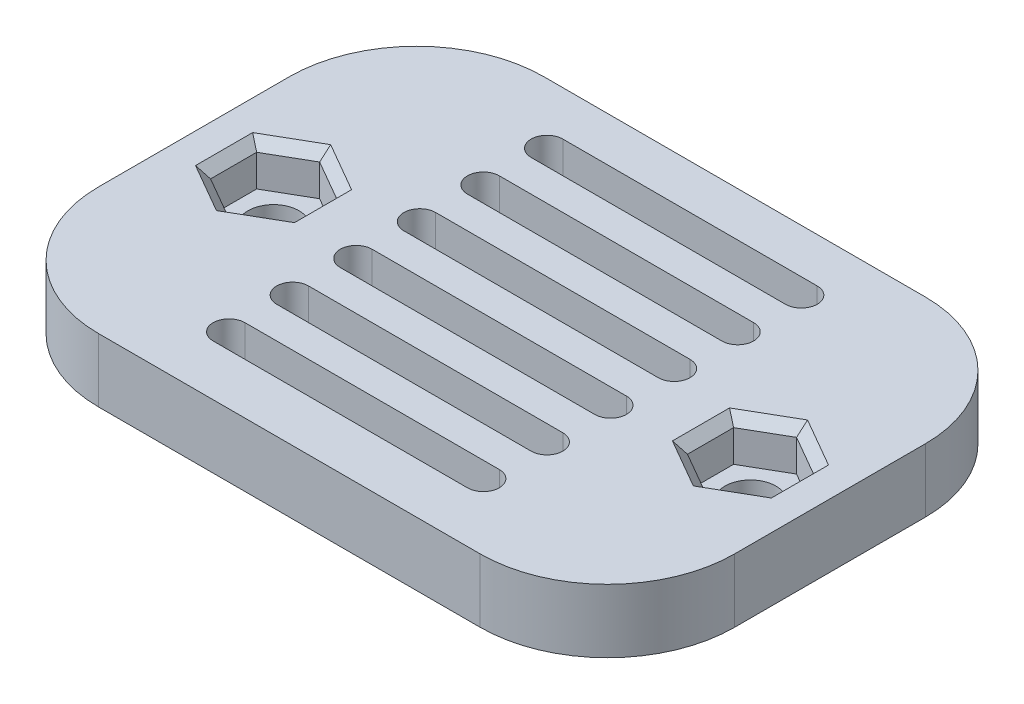
SolidWorks part; units mm, degrees
ref_plane "Alzado" through (0, 0, 0) normal (0, 0, 1) x (1, 0, 0)
ref_plane "Planta" through (0, 0, 0) normal (0, 1, 0) x (1, 0, 0)
ref_plane "Vista lateral" through (0, 0, 0) normal (1, 0, 0) x (0, 0, -1)
sketch "Croquis1" plane through (0, 0, 0) normal (0, 1, 0) x (1, 0, 0)
  line L1 (0, 0) -> (100, 0)
  line L2 (0, 0) -> (0, 70)
  line L3 (0, 70) -> (100, 70)
  line L4 (100, 0) -> (100, 70)
  dimension "D1" = 70
  dimension "D2" = 100
extrude "Saliente-Extruir1" add sketch "Croquis1" along normal blind 10
sketch "Croquis2" plane through (0, 10, 0) normal (0, 1, 0) x (1, 0, 0)
  line L0 (25, 70) -> (25, 0) construction
  line L1 (100, 70) -> (0, 70) construction
  line L2 (0, 0) -> (100, 0) construction
  line L3 (0, 70) -> (0, 0) construction
  line L4 (50, 70) -> (50, 0) construction
  line L5 (25, 70) -> (0, 70) construction
  line L6 (12.5, 70) -> (12.5, 0) construction
  line L7 (12.5, 35) -> (25, 35) construction
  line L9 (12.5, 42.25) -> (6.2213, 38.625)
  line L10 (6.2213, 38.625) -> (6.2213, 31.375)
  line L11 (6.2213, 31.375) -> (12.5, 27.75)
  line L12 (12.5, 27.75) -> (18.7787, 31.375)
  line L13 (18.7787, 31.375) -> (18.7787, 38.625)
  line L14 (18.7787, 38.625) -> (12.5, 42.25)
  circle A0 centre (12.5, 35) radius 6.2787 construction
  dimension "D1" = 25
  dimension "D2" = 14.5
extrude "Cortar-Extruir1" cut sketch "Croquis2" against normal blind 6.5
sketch "Croquis5" plane through (0, 10, 0) normal (0, 1, 0) x (1, 0, 0)
  circle A0 centre (12.5, 35) radius 4
extrude "Cortar-Extruir2" cut sketch "Croquis5" against normal up to surface (10 mm away) up to face at (50, 0, -35)
chamfer "Chaflán1" distance 1.5 angle 45 6 edges at (18.7787, 10, -35) (15.6393, 10, -29.5625) (9.3607, 10, -29.5625) (6.2213, 10, -35) (9.3607, 10, -40.4375) (15.6393, 10, -40.4375)
sketch "Croquis6" plane through (0, 10, 0) normal (0, 1, 0) x (1, 0, 0)
  line L0 (50, 70) -> (50, 0) construction
  line L1 (100, 70) -> (0, 70) construction
  line L2 (0, 0) -> (100, 0) construction
ref_plane "Plano1" through (50, 0, 0) normal (-1, 0, 0) x (0, 0, 1)
mirror "Simetría1" about plane through (50, 0, 0) normal (-1, 0, 0) of "Chaflán1", "Cortar-Extruir1", "Cortar-Extruir2"
fillet "Redondeo4" radius 20 1 edges at (100, 5, -70)
fillet "Redondeo5" radius 20 1 edges at (100, 5, 0)
fillet "Redondeo6" radius 20 1 edges at (0, 5, 0)
fillet "Redondeo7" radius 20 1 edges at (0, 5, -70)
sketch "Croquis7" plane through (0, 10, 0) normal (0, 1, 0) x (1, 0, 0)
  line L0 (50, 70) -> (50, 0) construction
  line L1 (80, 70) -> (20, 70) construction
  line L2 (20, 0) -> (80, 0) construction
  line L3 (25, 70) -> (25, 0) construction
  line L4 (75, 70) -> (75, 0) construction
  line L5 (30, 10.5) -> (70, 10.5) construction
  line L6 (30, 13) -> (70, 13)
  line L7 (30, 8) -> (70, 8)
  line L8 (30, 18) -> (70, 18)
  line L9 (30, 23) -> (70, 23)
  line L10 (30, 20.5) -> (70, 20.5) construction
  line L11 (30, 28) -> (70, 28)
  line L12 (30, 33) -> (70, 33)
  line L13 (30, 30.5) -> (70, 30.5) construction
  line L14 (30, 38) -> (70, 38)
  line L15 (30, 43) -> (70, 43)
  line L16 (30, 40.5) -> (70, 40.5) construction
  line L17 (30, 48) -> (70, 48)
  line L18 (30, 53) -> (70, 53)
  line L19 (30, 50.5) -> (70, 50.5) construction
  line L20 (30, 58) -> (70, 58)
  line L21 (30, 63) -> (70, 63)
  line L22 (30, 60.5) -> (70, 60.5) construction
  arc A0 (30, 13) -> (30, 8) centre (30, 10.5) ccw
  arc A1 (70, 8) -> (70, 13) centre (70, 10.5) ccw
  arc A2 (30, 23) -> (30, 18) centre (30, 20.5) ccw
  arc A3 (70, 18) -> (70, 23) centre (70, 20.5) ccw
  arc A4 (30, 33) -> (30, 28) centre (30, 30.5) ccw
  arc A5 (70, 28) -> (70, 33) centre (70, 30.5) ccw
  arc A6 (30, 43) -> (30, 38) centre (30, 40.5) ccw
  arc A7 (70, 38) -> (70, 43) centre (70, 40.5) ccw
  arc A8 (30, 53) -> (30, 48) centre (30, 50.5) ccw
  arc A9 (70, 48) -> (70, 53) centre (70, 50.5) ccw
  arc A10 (30, 63) -> (30, 58) centre (30, 60.5) ccw
  arc A11 (70, 58) -> (70, 63) centre (70, 60.5) ccw
  point P12 (50, 10.5)
  point P21 (50, 20.5)
  point P28 (50, 30.5)
  point P35 (50, 40.5)
  point P42 (50, 50.5)
  point P49 (50, 60.5)
  dimension "D3" = 5
  dimension "D4" = 5
  dimension "D1" = 25
  dimension "D2" = 25
  dimension "D5" = 5
  dimension "D6" = 8
  dimension "D7" = 6
extrude "Cortar-Extruir3" cut sketch "Croquis7" against normal up to surface (10 mm away) up to face at (87.5, 0, -39)
